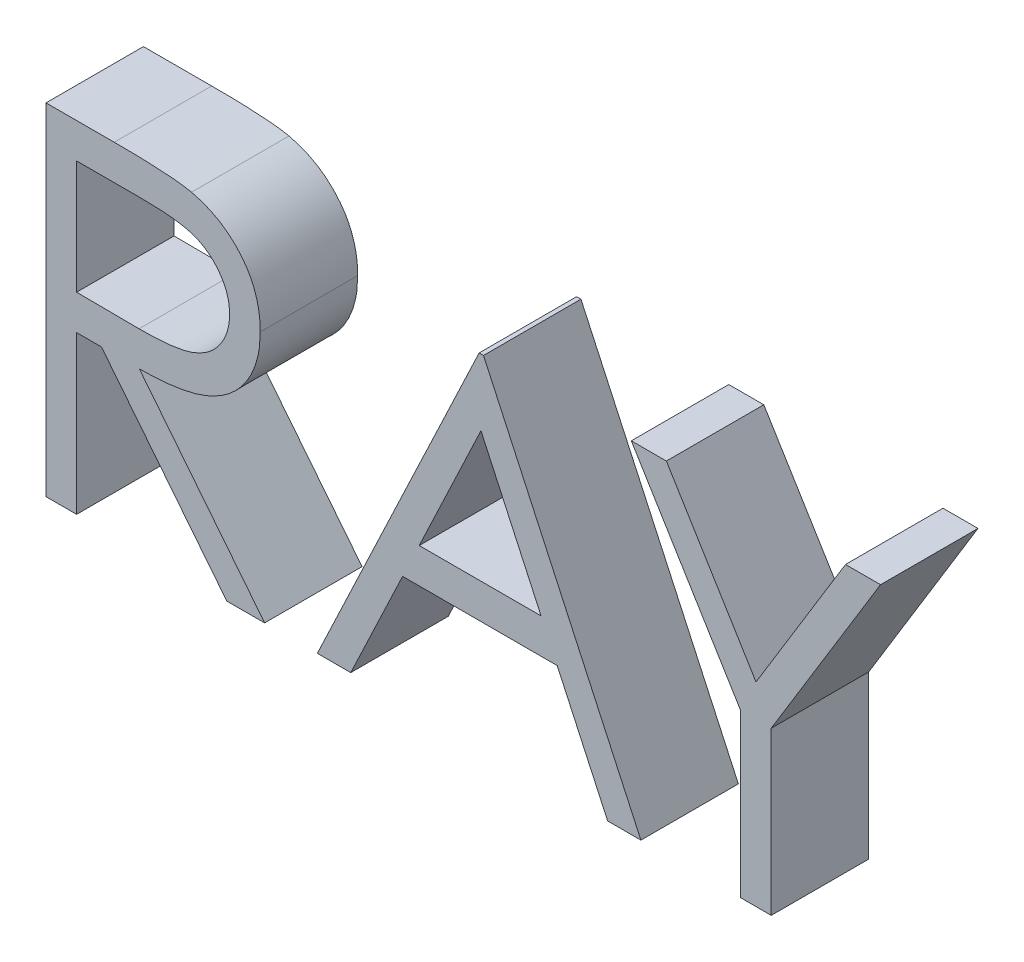
SolidWorks part; units mm, degrees
ref_plane "Front Plane" through (0, 0, 0) normal (0, 0, 1) x (1, 0, 0)
ref_plane "Top Plane" through (0, 0, 0) normal (0, 1, 0) x (1, 0, 0)
ref_plane "Right Plane" through (0, 0, 0) normal (1, 0, 0) x (0, 0, -1)
sketch "Sketch1" plane through (0, 0, 0) normal (0, 0, 1) x (1, 0, 0)
  text T0 "R"
extrude "Boss-Extrude1" add sketch "Sketch1" along normal blind 1
sketch "Sketch2" plane through (0, 0, 1) normal (0, 0, 1) x (1, 0, 0)
  text T0 "A"
  text T1 "Y"
extrude "Boss-Extrude2" add sketch "Sketch2" against normal blind 1 separate body
